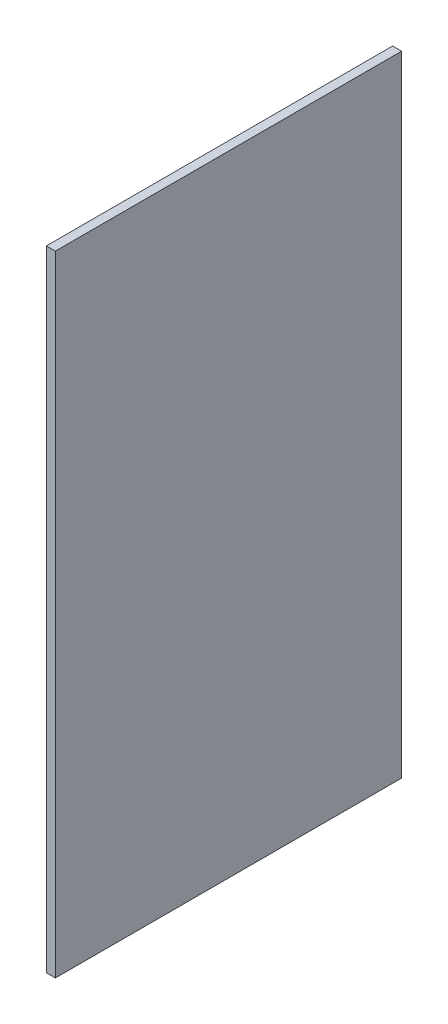
SolidWorks part; units mm, degrees
ref_plane "Front Plane" through (0, 0, 0) normal (0, 0, 1) x (1, 0, 0)
ref_plane "Top Plane" through (0, 0, 0) normal (0, 1, 0) x (1, 0, 0)
ref_plane "Right Plane" through (0, 0, 0) normal (1, 0, 0) x (0, 0, -1)
sketch "Sketch1" plane through (0, 0, 0) normal (1, 0, 0) x (0, 0, -1)
  line L1 (0, 0) -> (154, 0)
  line L2 (0, 0) -> (0, 280)
  line L3 (0, 280) -> (154, 280)
  line L4 (154, 0) -> (154, 280)
  dimension "D1" = 280
  dimension "D2" = 154
extrude "Boss-Extrude1" add sketch "Sketch1" along normal blind 4
